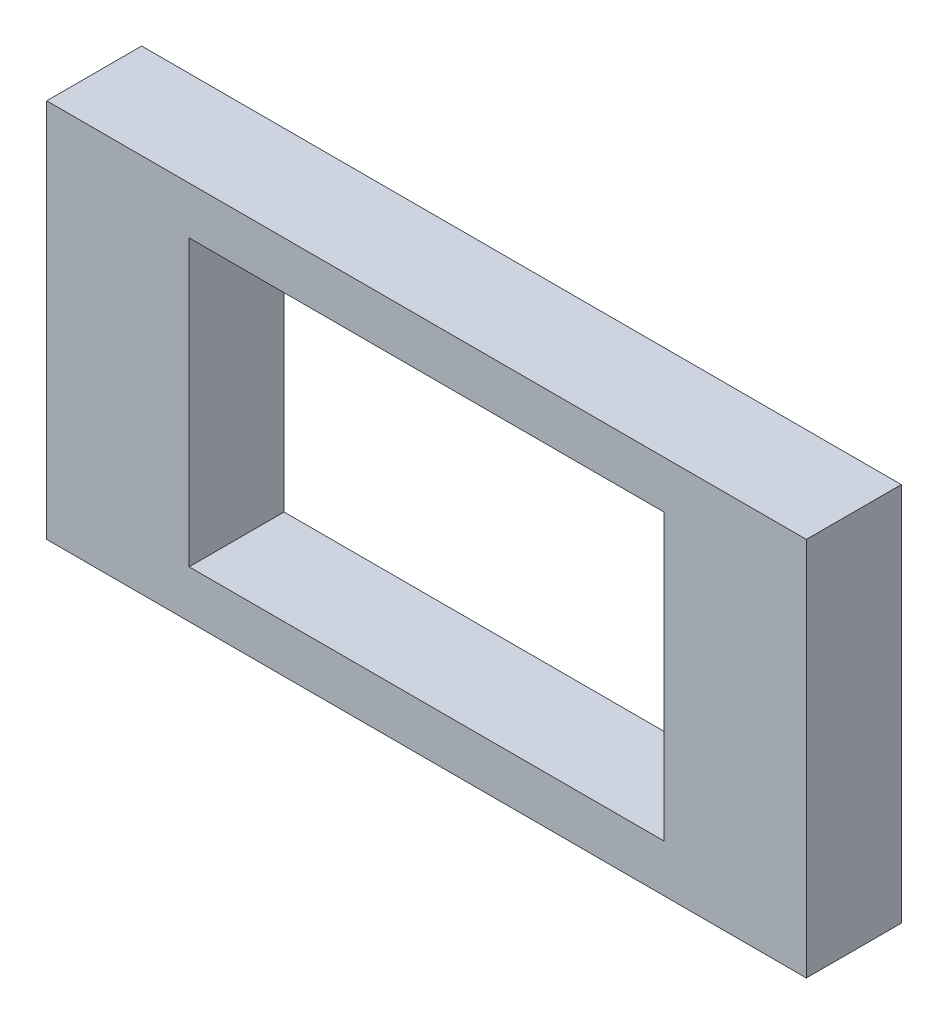
SolidWorks part; units mm, degrees
ref_plane "정면" through (0, 0, 0) normal (0, 0, 1) x (1, 0, 0)
ref_plane "윗면" through (0, 0, 0) normal (0, 1, 0) x (1, 0, 0)
ref_plane "우측면" through (0, 0, 0) normal (1, 0, 0) x (0, 0, -1)
sketch "스케치1" plane through (0, 0, 0) normal (0, 0, 1) x (1, 0, 0)
  line L0 (0, 0) -> (5.0188, 0) construction
  line L1 (0, 0.1211) -> (0, 4.6917) construction
  line L3 (-8, -4) -> (8, -4)
  line L4 (-8, -4) -> (-8, 4)
  line L5 (-8, 4) -> (8, 4)
  line L6 (8, -4) -> (8, 4)
  line L7 (-8, -4) -> (8, 4) construction
  line L8 (-8, 4) -> (8, -4) construction
  line L9 (-5, -3) -> (5, -3)
  line L10 (-5, -3) -> (-5, 3)
  line L11 (-5, 3) -> (5, 3)
  line L12 (5, -3) -> (5, 3)
  line L13 (-5, -3) -> (5, 3) construction
  line L14 (-5, 3) -> (5, -3) construction
  dimension "D1" = 16
  dimension "D2" = 8
  dimension "D3" = 6
  dimension "D4" = 10
extrude "보스-돌출1" add sketch "스케치1" along normal blind 2
